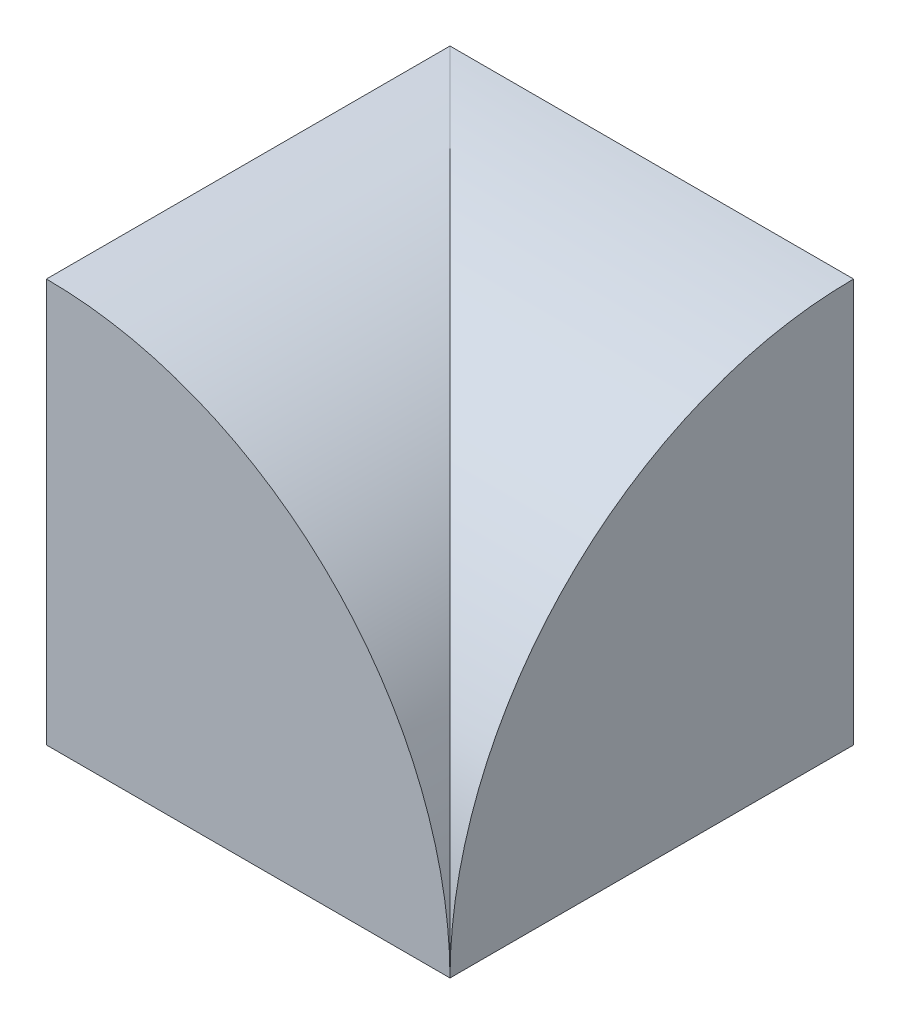
SolidWorks part; units mm, degrees
ref_plane "Ön Düzlem" through (0, 0, 0) normal (0, 0, 1) x (1, 0, 0)
ref_plane "Üst Düzlem" through (0, 0, 0) normal (0, 1, 0) x (1, 0, 0)
ref_plane "Sağ Düzlem" through (0, 0, 0) normal (1, 0, 0) x (0, 0, -1)
sketch "Çizim1" plane through (0, 0, 0) normal (0, 0, 1) x (1, 0, 0)
  line L0 (0, 20.5) -> (0, 0)
  line L1 (0, 0) -> (20.5, 0)
  arc A0 (20.5, 0) -> (0, 20.5) centre (0, 0) ccw
  dimension "D1" = 20.5
  dimension "D2" = 20.5
extrude "Yükseklik-Ekstrüzyon1" add sketch "Çizim1" along normal blind 20.5
sketch "Эскиз1" plane through (0, 0, 0) normal (-1, 0, 0) x (0, 0, 1)
  line L1 (20.5, 20.5) -> (0, 20.5) construction
  line L2 (20.5, 20.5) -> (20.5, 0) construction
  circle A0 centre (10.25, 10.25) radius 2.5
  dimension "D1" = 5
  dimension "D2" = 10.25
  dimension "D3" = 10.25
extrude "Бобышка-Вытянуть1" add sketch "Эскиз1" along normal blind 2.5
sketch "Эскиз2" plane through (0, 0, 0) normal (0, -1, 0) x (-1, 0, 0)
  line L0 (0, -20.5) -> (-20.5, -20.5) construction
  line L1 (-20.5, -20.5) -> (-20.5, 0) construction
  circle A0 centre (-10.25, -10.25) radius 2.5
  dimension "D1" = 5
  dimension "D2" = 10.25
  dimension "D3" = 10.25
extrude "Бобышка-Вытянуть2" add sketch "Эскиз2" along normal blind 2.5
sketch "Эскиз3" plane through (0, 0, 0) normal (0, 0, -1) x (-1, 0, 0)
  line L1 (0, 0) -> (-20.5, 0)
  line L2 (0, 0) -> (0, 20.5)
  line L3 (0, 20.5) -> (-20.5, 20.5)
  line L4 (-20.5, 0) -> (-20.5, 20.5)
  dimension "D1" = 0
  dimension "D2" = 0
revolve "Повернуть2" add sketch "Эскиз3" angle 90 about L1
sketch "Эскиз4" plane through (0, 0, 0) normal (0, 0, -1) x (-1, 0, 0)
  line L0 (0, 20.5) -> (-20.5, 20.5) construction
  line L1 (-20.5, 20.5) -> (-20.5, 0) construction
  circle A0 centre (-10.25, 10.25) radius 2.5
  dimension "D1" = 5
  dimension "D2" = 10.25
  dimension "D3" = 10.25
extrude "Бобышка-Вытянуть3" add sketch "Эскиз4" along normal blind 2.5
